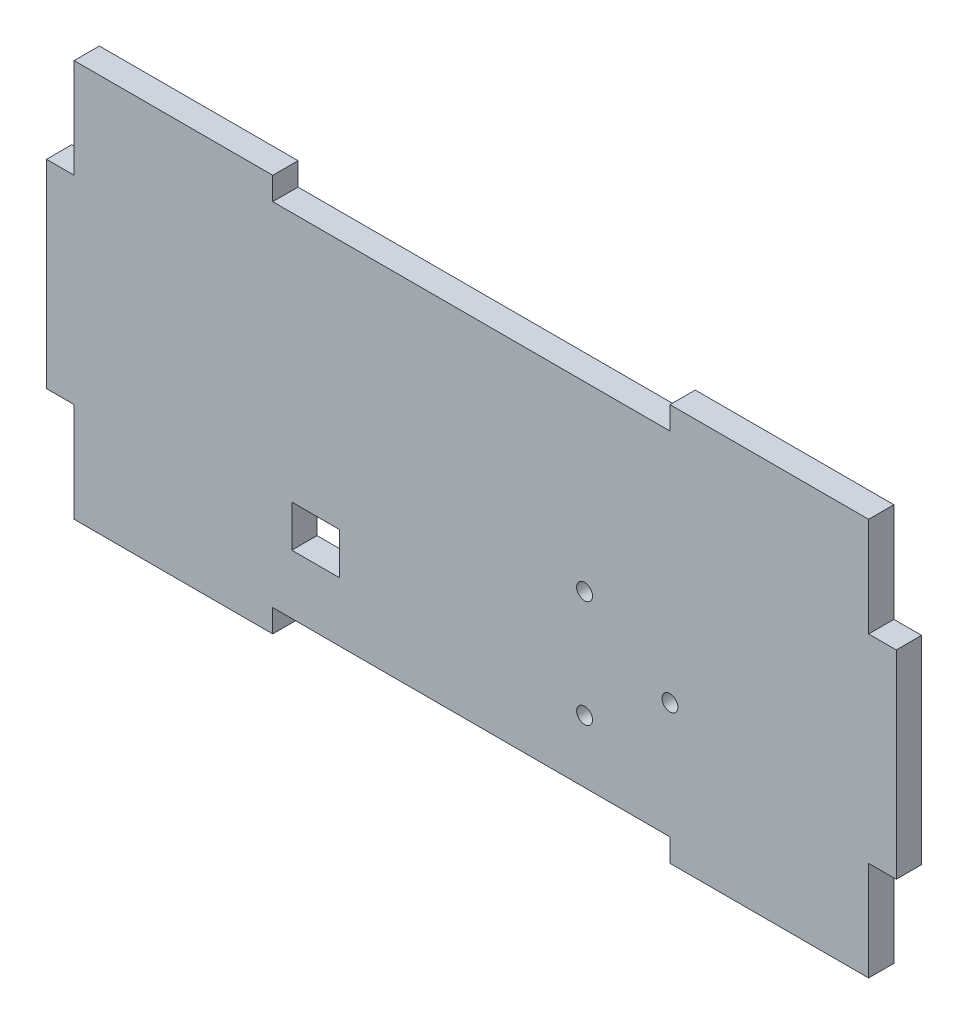
SolidWorks part; units mm, degrees
ref_plane "Front Plane" through (0, 0, 0) normal (0, 0, 1) x (1, 0, 0)
ref_plane "Top Plane" through (0, 0, 0) normal (0, 1, 0) x (1, 0, 0)
ref_plane "Right Plane" through (0, 0, 0) normal (1, 0, 0) x (0, 0, -1)
sketch "Sketch1" plane through (0, 0, 0) normal (0, 0, 1) x (1, 0, 0)
  line L1 (-100, 50) -> (100, 50)
  line L2 (-100, 50) -> (-100, -50)
  line L3 (-100, -50) -> (100, -50)
  line L4 (100, 50) -> (100, -50)
  line L5 (-100, 50) -> (100, -50) construction
  line L6 (-100, -50) -> (100, 50) construction
  point P0 (0, 0)
  dimension "D1" = 100
  dimension "D2" = 200
extrude "Boss-Extrude1" add sketch "Sketch1" along normal blind 6.36
sketch "Sketch2" [suppressed] plane through (0, 0, 3.36) normal (0, 0, 1) x (1, 0, 0)
  line L0 (50, 50) -> (-50, 50) construction
  line L1 (-25, 50) -> (25, 50)
  line L2 (-25, 50) -> (-25, 53.36)
  line L3 (-25, 53.36) -> (25, 53.36)
  line L4 (25, 50) -> (25, 53.36)
  line L5 (0, 0) -> (0, 53.36) construction
  line L6 (0, 0) -> (50, 0) construction
  line L7 (50, -50) -> (50, 50) construction
  dimension "D1" = 6.36
  dimension "D2" = 50
sketch "Sketch8" plane through (0, 0, 0) normal (0, 0, -1) x (-1, 0, 0)
  line L0 (0, 0) -> (0, 50) construction
  line L1 (-100, 50) -> (100, 50) construction
  line L2 (0, 0) -> (100, 0) construction
  line L3 (100, 50) -> (100, -50) construction
  line L5 (-50, 50) -> (50, 50)
  line L6 (-50, 50) -> (-50, 56.96)
  line L7 (-50, 56.96) -> (50, 56.96)
  line L8 (50, 50) -> (50, 56.96)
  dimension "D2" = 6.96
  dimension "D1" = 100
extrude "Boss-Extrude4" [suppressed] add sketch "Sketch8" against normal blind 6.36
mirror "Mirror4" [suppressed] about plane through (0, 0, 0) normal (0, 1, 0)
sketch "Sketch9" plane through (0, 0, 0) normal (0, 0, -1) x (-1, 0, 0)
  line L0 (0, 0) -> (100, 0) construction
  line L1 (100, 50) -> (100, -50) construction
  line L3 (100, 25) -> (106.96, 25)
  line L4 (100, 25) -> (100, -25)
  line L5 (100, -25) -> (106.96, -25)
  line L6 (106.96, 25) -> (106.96, -25)
  dimension "D1" = 50
  dimension "D2" = 6.96
extrude "Boss-Extrude5" add sketch "Sketch9" against normal blind 6.36
mirror "Mirror5" about plane through (0, 0, 0) normal (1, 0, 0) of "Boss-Extrude5"
sketch "Sketch10" plane through (0, 0, 6.36) normal (0, 0, 1) x (1, 0, 0)
  line L0 (0, 0) -> (0, 50) construction
  line L1 (100, 50) -> (-100, 50) construction
  line L3 (-50, 50) -> (50, 50)
  line L4 (-50, 50) -> (-50, 44.24)
  line L5 (-50, 44.24) -> (50, 44.24)
  line L6 (50, 50) -> (50, 44.24)
  dimension "D1" = 5.76
  dimension "D2" = 100
extrude "Cut-Extrude1" cut sketch "Sketch10" against normal through all and the other way through all
mirror "Mirror6" about plane through (0, 0, 0) normal (0, 1, 0) of "Cut-Extrude1"
sketch "Sketch11" plane through (0, 0, 6.36) normal (0, 0, 1) x (1, 0, 0)
  line L0 (0, 0) -> (100, 0) construction
  line L1 (100, -50) -> (100, -25) construction
  line L3 (100, 25) -> (94.24, 25)
  line L4 (100, 25) -> (100, -25)
  line L5 (100, -25) -> (94.24, -25)
  line L6 (94.24, 25) -> (94.24, -25)
  dimension "D2" = 50
  dimension "D1" = 5.76
extrude "Cut-Extrude2" [suppressed] cut sketch "Sketch11" against normal through all and the other way through all
mirror "Mirror7" [suppressed] about plane through (0, 0, 0) normal (1, 0, 0)
sketch "Sketch12" plane through (0, 0, 6.36) normal (0, 0, 1) x (1, 0, 0)
  line L0 (-100, -25) -> (-100, -50) construction
  line L1 (-100, -50) -> (-50, -50) construction
  line L2 (-75, -25) -> (-75, 23.3) construction
  line L3 (-22.6, 8) -> (-22.6, -19.9) construction
  circle A0 centre (-75, -25) radius 1.6
  circle A1 centre (-73.4, 23.3) radius 1.6
  circle A2 centre (-22.6, -19.9) radius 1.6
  circle A3 centre (-22.6, 8) radius 1.6
  dimension "D1" = 3.2
  dimension "D2" = 25
  dimension "D3" = 25
  dimension "D5" = 48.3
  dimension "D7" = 5.1
  dimension "D9" = 50.8
  dimension "D10" = 27.9
extrude "arduino holes" [suppressed] cut sketch "Sketch12" against normal through all and the other way through all
sketch "Sketch13" plane through (0, 0, 6.36) normal (0, 0, 1) x (1, 0, 0)
  line L0 (50, -15) -> (-18.2265, -15) construction
  line L1 (100, -50) -> (100, -25) construction
  line L2 (50, -50) -> (100, -50) construction
  circle A0 centre (50, -15) radius 2
  circle A1 centre (28.5, -1.5) radius 2
  circle A2 centre (28.5, -28.5) radius 2
  dimension "D1" = 4
  dimension "D2" = 27
  dimension "D3" = 21.5
  dimension "D4" = 50
  dimension "D5" = 35
extrude "battery holes" cut sketch "Sketch13" against normal blind 10
sketch "Sketch14" plane through (0, 0, 0) normal (0, 0, -1) x (-1, 0, 0)
  line L6 (33.2, -18.84) -> (45.2, -18.84)
  line L8 (45.2, -29.34) -> (33.2, -29.34)
  line L9 (45.2, -18.84) -> (45.2, -29.34)
  line L10 (33.2, -29.34) -> (33.2, -18.84)
  line L52 (50, -44.24) -> (50, -50)
  line L53 (50, -50) -> (100, -50)
  line L54 (100, -50) -> (100, -25)
  line L55 (100, -25) -> (106.96, -25)
  line L56 (106.96, -25) -> (106.96, 25)
  line L57 (106.96, 25) -> (100, 25)
  line L58 (100, 25) -> (100, 50)
  line L59 (100, 50) -> (50, 50)
  line L60 (50, 50) -> (50, 44.24)
  line L61 (50, 44.24) -> (-50, 44.24)
  line L62 (-50, 44.24) -> (-50, 50)
  line L63 (-50, 50) -> (-100, 50)
  line L64 (-100, 50) -> (-100, 25)
  line L65 (-100, 25) -> (-106.96, 25)
  line L66 (-106.96, 25) -> (-106.96, -25)
  line L67 (-106.96, -25) -> (-100, -25)
  line L68 (-100, -25) -> (-100, -50)
  line L69 (-100, -50) -> (-50, -50)
  line L70 (-50, -50) -> (-50, -44.24)
  line L71 (-50, -44.24) -> (50, -44.24)
  point P0 (-100, 50)
extrude "Cut-Extrude6" cut sketch "Sketch14" against normal through all contours L10 L8 L9 L6
equation "\"Sheet Thickness\"= 6.36mm"
equation "\"Height\"= 100mm"
equation "\"Length\"= 200mm"
equation "\"Width\"= 100mm"
equation "\"D1@Boss-Extrude1\"=\"Sheet Thickness\""
equation "\"D1@Sketch2\"=\"Sheet Thickness\""
equation "\"D2@Sketch2\"=\"Height\"/2"
equation "\"Kerf\"= .60mm"
equation "\"D2@Sketch9\"=\"Sheet Thickness\"+\"Kerf\""
equation "\"D1@Sketch9\"    = \"Height\"/2"
equation "\"D2@Sketch8\"=\"Sheet Thickness\"+\"Kerf\""
equation "\"D1@Sketch10\"=\"Sheet Thickness\"-\"Kerf\""
equation "\"D2@Sketch10\"   = \"Length\"/2"
equation "\"D1@Sketch11\"=\"Sheet Thickness\"-\"Kerf\""
equation "\"D2@Sketch11\"=\"Height\"/2"
